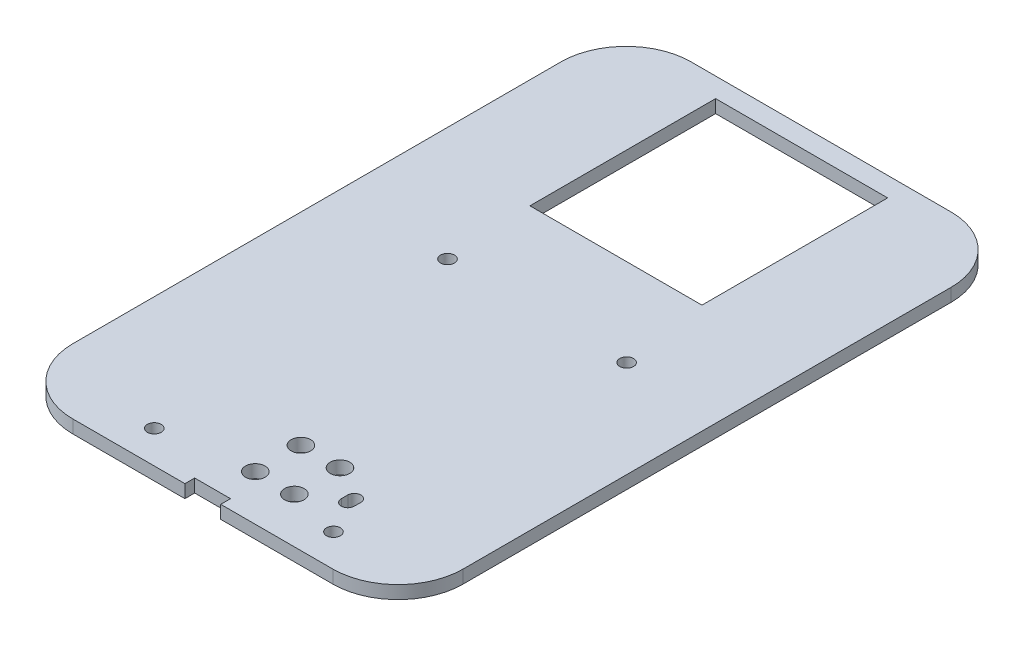
SolidWorks part; units mm, degrees
ref_plane "Front Plane" through (0, 0, 0) normal (0, 0, 1) x (1, 0, 0)
ref_plane "Top Plane" through (0, 0, 0) normal (0, 1, 0) x (1, 0, 0)
ref_plane "Right Plane" through (0, 0, 0) normal (1, 0, 0) x (0, 0, -1)
sketch "Sketch2" plane through (0, 0, 0) normal (0, 1, 0) x (1, 0, 0)
  line L0 (-25.3365, -60.2615) -> (25.3365, -60.2615)
  line L1 (-38.0365, -47.5615) -> (-38.0365, 47.5615)
  line L2 (38.0365, -47.5615) -> (38.0365, 47.5615)
  line L3 (-25.3365, 60.2615) -> (25.3365, 60.2615)
  line L4 (-38.0365, -60.2615) -> (38.0365, 60.2615) construction
  line L5 (38.0365, -60.2615) -> (-38.0365, 60.2615) construction
  arc A0 (-38.0365, 47.5615) -> (-25.3365, 60.2615) centre (-25.3365, 47.5615) cw
  arc A1 (38.0365, 47.5615) -> (25.3365, 60.2615) centre (25.3365, 47.5615) ccw
  arc A2 (25.3365, -60.2615) -> (38.0365, -47.5615) centre (25.3365, -47.5615) ccw
  arc A3 (-38.0365, -47.5615) -> (-25.3365, -60.2615) centre (-25.3365, -47.5615) ccw
  dimension "D3" = 12.7
  dimension "D4" = 12.7
  dimension "D1" = 120.523
  dimension "D2" = 76.073
extrude "top" add sketch "Sketch2" along normal blind 2.54
sketch "PCBOutline" plane through (0, 2.54, 2.54) normal (0, 1, 0) x (1, 0, 0)
  line L0 (-25.3365, -57.7215) -> (25.3365, -57.7215) construction
  line L1 (-18.9865, -55.1815) -> (22.9235, -55.1815)
  line L2 (-18.9865, -55.1815) -> (-18.9865, 9.5885)
  line L3 (-18.9865, 9.5885) -> (22.9235, 9.5885)
  line L4 (22.9235, -55.1815) -> (22.9235, 9.5885)
  line L5 (-38.0365, 50.1015) -> (-38.0365, -45.0215) construction
  dimension "D1" = 41.91
  dimension "D2" = 64.77
  dimension "D3" = 2.54
  dimension "D4" = 19.05
sketch "Sketch7" plane through (0, 2.54, 0) normal (0, 1, 0) x (1, 0, 0)
  line L1 (1.3335, -51.3715) -> (8.9535, -51.3715) construction
  line L2 (1.3335, -51.3715) -> (1.3335, -42.4815) construction
  line L3 (-18.9865, -57.7215) -> (-18.9865, 7.0485) construction
  line L4 (15.5575, -46.2915) -> (15.5575, -47.5615) construction
  line L5 (16.8275, -46.2915) -> (16.8275, -47.5615)
  line L6 (14.2875, -46.2915) -> (14.2875, -47.5615)
  line L7 (1.3335, -46.9265) -> (15.5575, -46.9265) construction
  line L8 (-18.9865, -57.7215) -> (22.9235, -57.7215) construction
  circle A0 centre (1.3335, -51.3715) radius 1.905
  circle A1 centre (8.9535, -51.3715) radius 1.905
  circle A2 centre (8.9535, -42.4815) radius 1.905
  circle A3 centre (1.3335, -42.4815) radius 1.905
  arc A4 (16.8275, -46.2915) -> (14.2875, -46.2915) centre (15.5575, -46.2915) ccw
  arc A5 (14.2875, -47.5615) -> (16.8275, -47.5615) centre (15.5575, -47.5615) ccw
  point P6 (15.5575, -46.9265)
  dimension "D7" = 3.81
  dimension "D4" = 7.62
  dimension "D5" = 8.89
  dimension "D6" = 20.32
  dimension "D8" = 14.224
  dimension "D9" = 1.27
  dimension "D10" = 2.54
  dimension "D11" = 6.35
  dimension "D2" = 2
  dimension "D3" = 2
extrude "ButtonLEDCut" cut sketch "Sketch7" against normal through all
sketch "Sketch8" plane through (0, 2.54, 0) normal (0, 1, 0) x (1, 0, 0)
  line L0 (0, 0) -> (0, 60.2615) construction
  line L1 (25.3365, 60.2615) -> (-25.3365, 60.2615) construction
  line L2 (-16.764, 20.2565) -> (-16.764, 56.4515)
  line L3 (-16.764, 20.2565) -> (16.764, 20.2565)
  line L4 (-16.764, 56.4515) -> (16.764, 56.4515)
  line L5 (16.764, 20.2565) -> (16.764, 56.4515)
  line L6 (-16.764, 20.2565) -> (16.764, 56.4515) construction
  line L7 (-16.764, 56.4515) -> (16.764, 20.2565) construction
  line L8 (-16.764, 22.1615) -> (16.764, 22.1615) construction
  point P6 (0, 38.354)
  dimension "D1" = 3.81
  dimension "D2" = 33.528
  dimension "D3" = 34.29
  dimension "D4" = 36.195
extrude "SolarCut" cut sketch "Sketch8" against normal through all
sketch "Mounting Holes" plane through (0, 2.54, 2.54) normal (0, 1, 0) x (1, 0, 0)
  line L2 (-18.9865, -55.1815) -> (-18.9865, 9.5885) construction
  line L3 (-18.9865, -55.1815) -> (22.9235, -55.1815) construction
  point P0 (-15.8115, 5.7785)
  point P2 (19.1135, 5.7785)
  point P4 (19.1135, -51.3715)
  point P6 (-15.8115, -51.3715)
  dimension "D1" = 3.175
  dimension "D2" = 3.81
  dimension "D3" = 34.925
  dimension "D4" = 57.15
hole_wizard "#6-32 Tapped Hole1" positions "Sketch12" profile "Sketch11" tap size "#6-32" standard "ANSI Inch"
sketch "Sketch12" plane through (0, 2.54, 0) normal (0, 1, 0) x (1, 0, 0)
  point P0 (-15.8115, 3.2385)
  point P3 (19.1135, 3.2385)
  point P6 (19.1135, -53.9115)
  point P9 (-15.8115, -53.9115)
sketch "Sketch11" plane through (-15.8115, 2.54, -3.2385) normal (1, 0, 0) x (0, 0, 1)
  line L0 (0, 0) -> (0, 11.9887)
  line L1 (0, 11.9887) -> (1.3525, 11.176)
  line L2 (1.3525, 11.176) -> (1.3525, 0)
  line L5 (1.3525, 0) -> (0, 0)
  line L10 (0, 11.9887) -> (-1.3526, 11.176) construction
  line L11 (0, -6.35) -> (0, 107.95) construction
  dimension "Tap Drill Dia." = 2.7051
  dimension "Tap Drill Depth" = 11.176
  dimension "Drill Angle" = 118
sketch "Sketch13" plane through (0, 0, -60.2615) normal (0, 0, -1) x (-1, 0, 0)
  line L0 (-25.3365, 0) -> (25.3365, 0) construction
  line L1 (-18.923, 0) -> (-6.477, 0)
  line L2 (-18.923, 0) -> (-18.923, 1.27)
  line L3 (-18.923, 1.27) -> (-6.477, 1.27)
  line L4 (-6.477, 0) -> (-6.477, 1.27)
  line L5 (0, 0) -> (0, 2.54) construction
  line L6 (-25.3365, 2.54) -> (25.3365, 2.54) construction
  line L7 (18.923, 0) -> (6.477, 0)
  line L8 (6.477, 0) -> (6.477, 1.27)
  line L9 (18.923, 1.27) -> (6.477, 1.27)
  line L10 (18.923, 0) -> (18.923, 1.27)
  dimension "D1" = 6.477
  dimension "D2" = 1.27
  dimension "D3" = 12.446
extrude "Body Tabs" add sketch "Sketch13" along normal blind 1.27 draft 7
sketch "Sketch14" plane through (0, 2.54, 0) normal (0, 1, 0) x (1, 0, 0)
  line L0 (0, -60.2615) -> (0, -56.9665) construction
  line L1 (-25.3365, -60.2615) -> (25.3365, -60.2615) construction
  line L3 (-3.4925, -60.2615) -> (3.4925, -60.2615)
  line L4 (-3.4925, -60.2615) -> (-3.4925, -58.3565)
  line L5 (-3.4925, -58.3565) -> (3.4925, -58.3565)
  line L6 (3.4925, -60.2615) -> (3.4925, -58.3565)
  dimension "D1" = 6.985
  dimension "D2" = 1.905
extrude "Flat Head Hole" cut sketch "Sketch14" against normal through all
sketch "Sketch15" plane through (0, 0, 60.2615) normal (0, 0, 1) x (1, 0, 0)
  line L0 (0, 0) -> (0, 2.54) construction
  line L1 (-12.7, 1.651) -> (-6.35, 1.651)
  line L2 (-12.7, 1.651) -> (-12.7, 0.889)
  line L3 (-12.7, 0.889) -> (-6.35, 0.889)
  line L4 (-6.35, 1.651) -> (-6.35, 0.889)
  line L5 (3.4925, 2.54) -> (-3.4925, 2.54) construction
  line L6 (0, 1.27) -> (-25.3365, 1.27) construction
  line L7 (-25.3365, 2.54) -> (-25.3365, 0) construction
  line L8 (-25.3365, 1.27) -> (25.3365, 1.27) construction
  line L9 (25.3365, 2.54) -> (25.3365, 0) construction
  line L10 (12.7, 1.651) -> (12.7, 0.889)
  line L11 (12.7, 0.889) -> (6.35, 0.889)
  line L12 (6.35, 1.651) -> (6.35, 0.889)
  line L13 (12.7, 1.651) -> (6.35, 1.651)
  point P16 (-6.35, 1.27)
  dimension "D1" = 0.762
  dimension "D2" = 6.35
  dimension "D3" = 6.35
extrude "Hold Grpoves" [suppressed] cut sketch "Sketch15" against normal blind 0.381
fillet "Hold Fillets" [suppressed] radius 0.381
